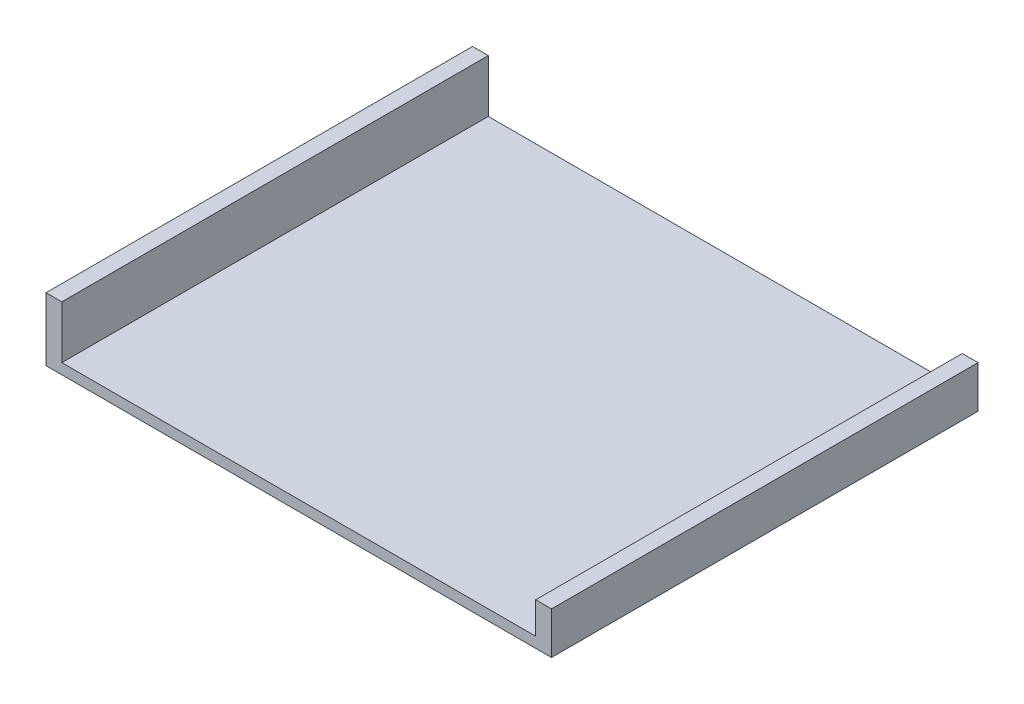
SolidWorks part; units mm, degrees
ref_plane "Front Plane" through (0, 0, 0) normal (0, 0, 1) x (1, 0, 0)
ref_plane "Top Plane" through (0, 0, 0) normal (0, 1, 0) x (1, 0, 0)
ref_plane "Right Plane" through (0, 0, 0) normal (1, 0, 0) x (0, 0, -1)
sketch "SK_P01_Tray" plane through (0, 0, 0) normal (0, 1, 0) x (1, 0, 0)
  line L0 (-48, -40.5) -> (48, -40.5)
  line L1 (48, -40.5) -> (48, 40.5)
  line L2 (48, 40.5) -> (-48, 40.5)
  line L3 (-48, 40.5) -> (-48, -40.5)
extrude "P01_Tray" add sketch "SK_P01_Tray" along normal blind 2
sketch "SK_P02_Rearstop" plane through (0, 0, 0) normal (0, 1, 0) x (1, 0, 0)
  line L0 (-48, -40.5) -> (-45, -40.5)
  line L1 (-45, -40.5) -> (-45, 40.5)
  line L2 (-45, 40.5) -> (-48, 40.5)
  line L3 (-48, 40.5) -> (-48, -40.5)
extrude "P02_Rearstop" add sketch "SK_P02_Rearstop" along normal blind 10 from offset 2
sketch "SK_P03_Frontlip" plane through (0, 0, 0) normal (0, 1, 0) x (1, 0, 0)
  line L0 (45, -40.5) -> (48, -40.5)
  line L1 (48, -40.5) -> (48, 40.5)
  line L2 (48, 40.5) -> (45, 40.5)
  line L3 (45, 40.5) -> (45, -40.5)
extrude "P03_Frontlip" add sketch "SK_P03_Frontlip" along normal blind 6 from offset 2
